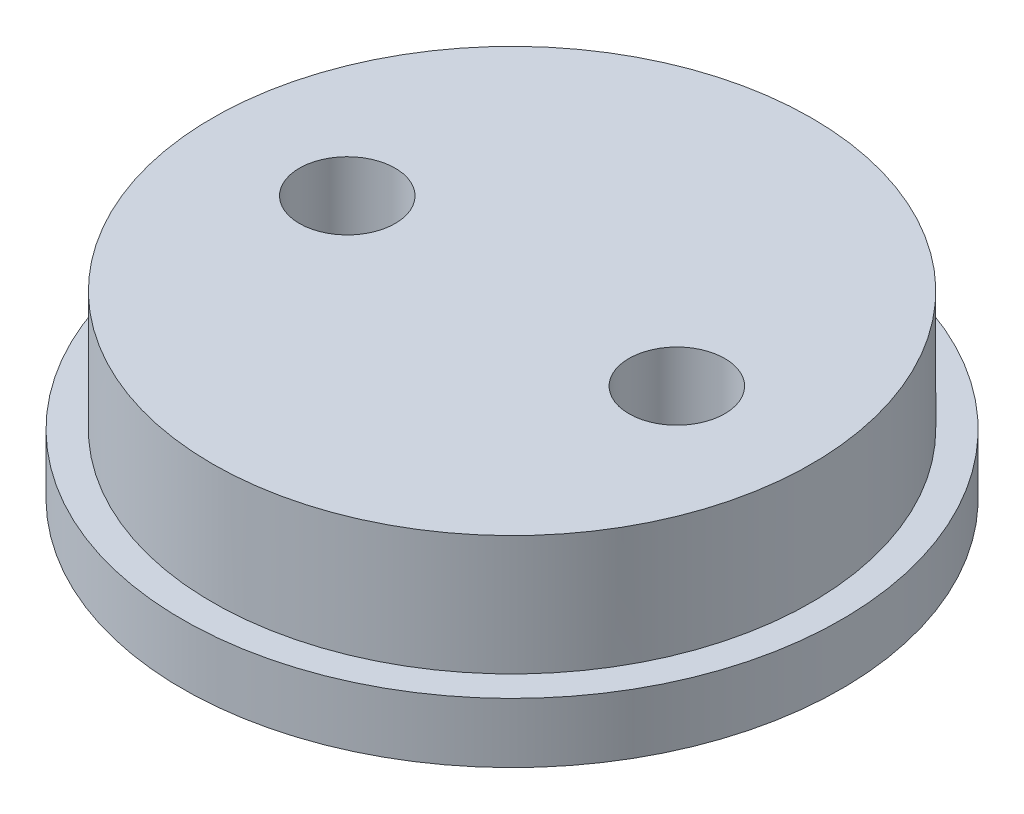
SolidWorks part; units mm, degrees
ref_plane "Front Plane" through (0, 0, 0) normal (0, 0, 1) x (1, 0, 0)
ref_plane "Top Plane" through (0, 0, 0) normal (0, 1, 0) x (1, 0, 0)
ref_plane "Right Plane" through (0, 0, 0) normal (1, 0, 0) x (0, 0, -1)
sketch "Sketch1" plane through (0, 0, 0) normal (0, 1, 0) x (1, 0, 0)
  circle A0 centre (0, 0) radius 10
  dimension "D1" = 20
extrude "Boss-Extrude1" add sketch "Sketch1" along normal blind 6
sketch "Sketch4" plane through (0, 0, 0) normal (0, -1, 0) x (1, 0, 0)
  circle A0 centre (0, 0) radius 11
  dimension "D1" = 22
extrude "Boss-Extrude2" add sketch "Sketch4" against normal blind 2
sketch "Sketch3" plane through (0, 0, 0) normal (0, 1, 0) x (1, 0, 0)
  line L0 (0, 8.0571) -> (0, -8.4294) construction
  circle A2 centre (0, 0) radius 5.5 construction
  circle A3 centre (-5.5, 0) radius 1.6
  circle A4 centre (5.5, 0) radius 1.6
  circle A5 centre (-5.5, 0) radius 3 construction
  circle A6 centre (5.5, 0) radius 3.5935 construction
  dimension "D1" = 11
  dimension "D2" = 6
  dimension "D3" = 3.2
extrude "Cut-Extrude2" cut sketch "Sketch3" along normal blind 15
